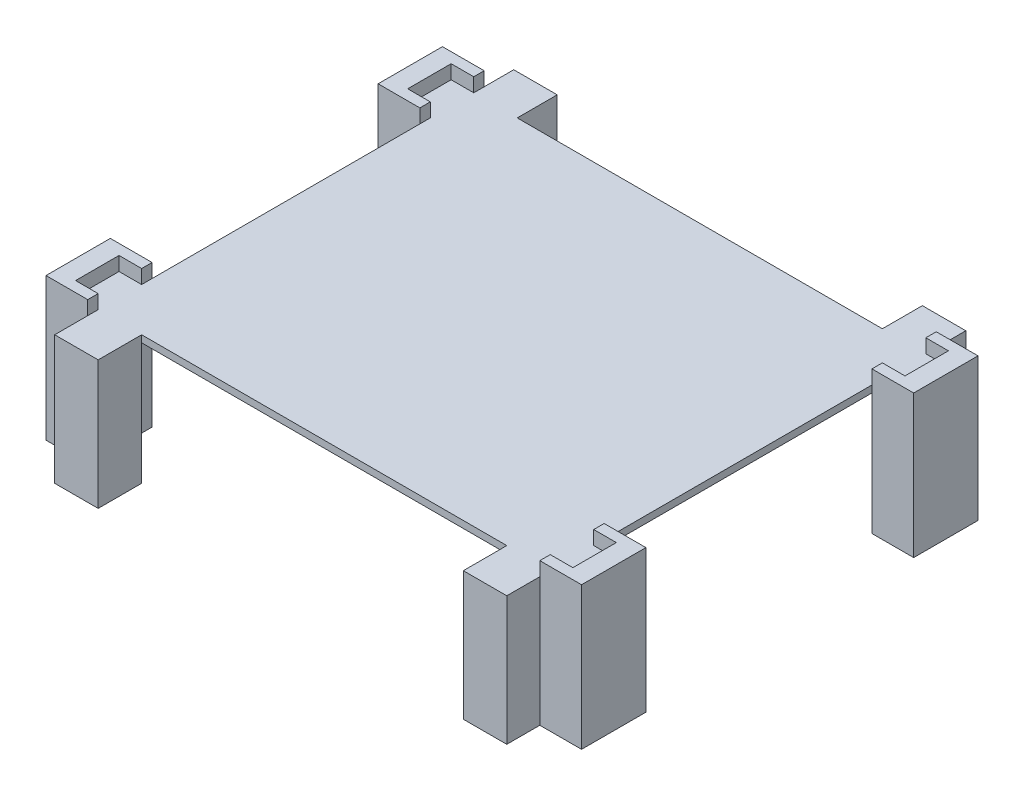
SolidWorks part; units mm, degrees
ref_plane "Front Plane" through (0, 0, 0) normal (0, 0, 1) x (1, 0, 0)
ref_plane "Top Plane" through (0, 0, 0) normal (0, 1, 0) x (1, 0, 0)
ref_plane "Right Plane" through (0, 0, 0) normal (1, 0, 0) x (0, 0, -1)
sketch "Sketch1" plane through (0, 0, 0) normal (0, 1, 0) x (1, 0, 0)
  line L0 (3, 0) -> (3, 3) construction
  line L1 (0, 0) -> (130, 0)
  line L2 (0, 0) -> (0, 108)
  line L3 (0, 108) -> (130, 108)
  line L4 (130, 0) -> (130, 108)
  line L5 (125.5, 108) -> (125.5, 105) construction
  line L6 (125.5, 105) -> (97.5, 105) construction
  line L8 (0, 0) -> (12.5, 0)
  line L9 (0, 0) -> (0, -12.5)
  line L10 (0, -12.5) -> (12.5, -12.5)
  line L11 (12.5, 0) -> (12.5, -12.5)
  line L12 (130, 0) -> (117.5, 0)
  line L13 (130, 0) -> (130, -12.5)
  line L14 (130, -12.5) -> (117.5, -12.5)
  line L15 (117.5, 0) -> (117.5, -12.5)
  line L16 (0, 108) -> (12.5, 108)
  line L17 (0, 108) -> (0, 119.5)
  line L18 (0, 119.5) -> (12.5, 119.5)
  line L19 (12.5, 108) -> (12.5, 119.5)
  line L20 (130, 108) -> (117.5, 108)
  line L21 (130, 108) -> (130, 119.5)
  line L22 (130, 119.5) -> (117.5, 119.5)
  line L23 (117.5, 108) -> (117.5, 119.5)
  circle A0 centre (3, 3) radius 1
  circle A1 centre (125.5, 105) radius 1
  circle A2 centre (97.5, 105) radius 1
  circle A3 centre (3, 3) radius 2
  circle A4 centre (97.5, 105) radius 2
  circle A5 centre (125.5, 105) radius 2
  point P7 (3, 1.5)
  point P11 (125.5, 106.5)
  point P30 (0, 0)
  dimension "D5" = 2
  dimension "D8" = 2
  dimension "D10" = 2
  dimension "D11" = 4
  dimension "D12" = 4
  dimension "D13" = 4
  dimension "D1" = 130
  dimension "D2" = 108
  dimension "D3" = 3
  dimension "D4" = 3
  dimension "D6" = 3
  dimension "D7" = 4.5
  dimension "D9" = 28
  dimension "D14" = 12.5
  dimension "D15" = 12.5
  dimension "D16" = 12.5
  dimension "D17" = 12.5
  dimension "D18" = 11.5
  dimension "D19" = 12.5
  dimension "D20" = 11.5
  dimension "D21" = 12.5
sketch "Sketch9" plane through (0, 3, 0) normal (0, 1, 0) x (1, 0, 0)
  line L7 (0, 0) -> (-6.5, 0)
  line L8 (0, 0) -> (0, 12.5)
  line L9 (0, 12.5) -> (-6.5, 12.5)
  line L10 (-6.5, 0) -> (-6.5, 12.5)
  line L11 (0, 108) -> (-6.5, 108)
  line L12 (0, 108) -> (0, 95.5)
  line L13 (0, 95.5) -> (-6.5, 95.5)
  line L14 (-6.5, 108) -> (-6.5, 95.5)
  line L15 (130, 0) -> (136.5, 0)
  line L16 (130, 0) -> (130, 12.5)
  line L17 (130, 12.5) -> (136.5, 12.5)
  line L18 (136.5, 0) -> (136.5, 12.5)
  line L19 (130, 108) -> (136.5, 108)
  line L20 (130, 108) -> (130, 95.5)
  line L21 (130, 95.5) -> (136.5, 95.5)
  line L22 (136.5, 108) -> (136.5, 95.5)
  line L43 (130, 12.5) -> (142, 12.5)
  line L44 (130, 12.5) -> (130, 15.5)
  line L45 (130, 15.5) -> (142, 15.5)
  line L46 (142, 12.5) -> (142, 15.5)
  line L47 (130, 0) -> (142, 0)
  line L48 (130, 0) -> (130, -3)
  line L49 (130, -3) -> (142, -3)
  line L50 (142, 0) -> (142, -3)
  line L51 (0, 0) -> (-12, 0)
  line L52 (0, 0) -> (0, -3)
  line L53 (0, -3) -> (-12, -3)
  line L54 (-12, 0) -> (-12, -3)
  line L55 (0, 12.5) -> (-12, 12.5)
  line L56 (0, 12.5) -> (0, 15.5)
  line L57 (0, 15.5) -> (-12, 15.5)
  line L58 (-12, 12.5) -> (-12, 15.5)
  line L59 (0, 95.5) -> (-12, 95.5)
  line L60 (0, 95.5) -> (0, 92.5)
  line L61 (0, 92.5) -> (-12, 92.5)
  line L62 (-12, 95.5) -> (-12, 92.5)
  line L63 (0, 108) -> (-12, 108)
  line L64 (0, 108) -> (0, 111)
  line L65 (0, 111) -> (-12, 111)
  line L66 (-12, 108) -> (-12, 111)
  line L67 (130, 108) -> (142, 108)
  line L68 (130, 108) -> (130, 111)
  line L69 (130, 111) -> (142, 111)
  line L70 (142, 108) -> (142, 111)
  line L71 (130, 95.5) -> (142, 95.5)
  line L72 (130, 95.5) -> (130, 92.5)
  line L73 (130, 92.5) -> (142, 92.5)
  line L74 (142, 95.5) -> (142, 92.5)
  line L75 (136.5, 0) -> (142, 0)
  line L76 (136.5, 0) -> (136.5, 12.5)
  line L77 (136.5, 12.5) -> (142, 12.5)
  line L78 (142, 0) -> (142, 12.5)
  line L79 (136.5, 95.5) -> (142, 95.5)
  line L80 (136.5, 95.5) -> (136.5, 108)
  line L81 (136.5, 108) -> (142, 108)
  line L82 (142, 95.5) -> (142, 108)
  line L83 (-6.5, 108) -> (-12, 108)
  line L84 (-6.5, 108) -> (-6.5, 95.5)
  line L85 (-6.5, 95.5) -> (-12, 95.5)
  line L86 (-12, 108) -> (-12, 95.5)
  line L87 (-6.5, 12.5) -> (-12, 12.5)
  line L88 (-6.5, 12.5) -> (-6.5, 0)
  line L89 (-6.5, 0) -> (-12, 0)
  line L90 (-12, 12.5) -> (-12, 0)
  dimension "D1" = 6.5
  dimension "D2" = 12.5
  dimension "D3" = 6.5
  dimension "D4" = 12.5
  dimension "D5" = 6.5
  dimension "D6" = 12.5
  dimension "D7" = 6.5
  dimension "D8" = 12.5
  dimension "D10" = 12
  dimension "D11" = 3
  dimension "D12" = 3
  dimension "D13" = 12
  dimension "D14" = 3
  dimension "D16" = 3
  dimension "D17" = 12
  dimension "D18" = 3
  dimension "D20" = 3
  dimension "D21" = 12
  dimension "D22" = 3
  dimension "D24" = 3
extrude "Boss-Extrude1" add sketch "Sketch9" along normal blind 4 contours L51 L54 L53 L52 L7 | L55 L90 L51 L10 | L58 L55 L9 L56 L57 | L43 L46 L45 L44 L17 | L47 L78 L43 L18 | L50 L47 L15 L48 L49 | L74 L71 L21 L72 L73 | L71 L82 L67 L22 | L67 L70 L69 L68 L19 | L59 L62 L61 L60 L13 | L63 L86 L59 L14 | L66 L63 L11 L64 L65
sketch "Sketch11" plane through (0, 3, 0) normal (0, -1, 0) x (1, 0, 0)
  line L1 (0, 3) -> (-12, 3)
  line L2 (0, 3) -> (0, -15.5)
  line L3 (0, -15.5) -> (-12, -15.5)
  line L4 (-12, 3) -> (-12, -15.5)
  line L5 (130, 3) -> (142, 3)
  line L6 (130, 3) -> (130, -15.5)
  line L7 (130, -15.5) -> (142, -15.5)
  line L8 (142, 3) -> (142, -15.5)
  line L9 (142, -111) -> (130, -111)
  line L10 (142, -111) -> (142, -92.5)
  line L11 (142, -92.5) -> (130, -92.5)
  line L12 (130, -111) -> (130, -92.5)
  line L13 (0, -111) -> (-12, -111)
  line L14 (0, -111) -> (0, -92.5)
  line L15 (0, -92.5) -> (-12, -92.5)
  line L16 (-12, -111) -> (-12, -92.5)
  line L17 (0, -108) -> (130, -108)
  line L18 (0, -108) -> (0, 0)
  line L19 (0, 0) -> (130, 0)
  line L20 (130, -108) -> (130, 0)
  line M5 (-6.5, 0) -> (0, 0)
  line M6 (0, 0) -> (0, 3)
  line M7 (0, 3) -> (-12, 3)
  line M8 (-12, 3) -> (-12, -15.5)
  line M9 (-12, -15.5) -> (0, -15.5)
  line M10 (0, -15.5) -> (0, -12.5)
  line M11 (0, -12.5) -> (-6.5, -12.5)
  line M12 (-6.5, -12.5) -> (-6.5, 0)
extrude "Boss-Extrude2" add sketch "Sketch11" along normal blind 2 contours L12 L20 L6 L19 L2 L18 L14 L17 M10 | L2 M5 M12 M11 | M12 M5 M6 M7 M8 M9 M10 M11 | L8 L5 L6 L7 | L12 L9 L10 L11 | L16 L13 L14 L15
sketch "Sketch12" plane through (0, 1, 0) normal (0, -1, 0) x (1, 0, 0)
  line L1 (130, 0) -> (117.5, 0)
  line L2 (130, 0) -> (130, 12.5)
  line L3 (130, 12.5) -> (117.5, 12.5)
  line L4 (117.5, 0) -> (117.5, 12.5)
  line L5 (130, -108) -> (117.5, -108)
  line L6 (130, -108) -> (130, -119.5)
  line L7 (130, -119.5) -> (117.5, -119.5)
  line L8 (117.5, -108) -> (117.5, -119.5)
  line L9 (0, -108) -> (12.5, -108)
  line L10 (0, -108) -> (0, -119.5)
  line L11 (0, -119.5) -> (12.5, -119.5)
  line L12 (12.5, -108) -> (12.5, -119.5)
  line L13 (12.5, 0) -> (0, 0)
  line L14 (12.5, 0) -> (12.5, 12.5)
  line L15 (12.5, 12.5) -> (0, 12.5)
  line L16 (0, 0) -> (0, 12.5)
  line M9 (130, 0) -> (0, 0)
  line M10 (0, 0) -> (0, 3)
  line M18 (0, -111) -> (0, -108)
  line M19 (0, -108) -> (130, -108)
  line M20 (130, -108) -> (130, -111)
  line M28 (130, 3) -> (130, 0)
extrude "Boss-Extrude3" add sketch "Sketch12" against normal blind 2 contours L12 L10 L11 M19 M18 | L16 L14 L15 M10 M9 | L4 L2 L3 M9 M28 | L8 L7 L6 M19 M20
sketch "Sketch13" plane through (0, 1, 0) normal (0, -1, 0) x (-1, 0, 0)
  line L0 (-142, -3) -> (-142, 15.5) construction
  line L1 (0, -12.5) -> (-12.5, -12.5)
  line L2 (0, -12.5) -> (0, 0)
  line L3 (0, 0) -> (-12.5, 0)
  line L4 (-12.5, -12.5) -> (-12.5, 0)
  line L5 (12, -3) -> (0, -3)
  line L6 (12, -3) -> (12, 15.5)
  line L7 (12, 15.5) -> (0, 15.5)
  line L8 (0, -3) -> (0, 15.5)
  line L9 (0, 0) -> (-130, 0)
  line L10 (0, 0) -> (0, 108)
  line L11 (0, 108) -> (-130, 108)
  line L12 (-130, 0) -> (-130, 108)
  line L13 (-117.5, 108) -> (-130, 108)
  line L14 (-117.5, 108) -> (-117.5, 119.5)
  line L15 (-117.5, 119.5) -> (-130, 119.5)
  line L16 (-130, 108) -> (-130, 119.5)
  line L17 (-130, 92.5) -> (-142, 92.5)
  line L18 (-130, 92.5) -> (-130, 111)
  line L19 (-130, 111) -> (-142, 111)
  line L20 (-142, 92.5) -> (-142, 111)
  line L21 (-130, -3) -> (-142, -3)
  line L22 (-130, -3) -> (-130, 15.5)
  line L23 (-130, 15.5) -> (-142, 15.5)
  line L24 (-142, -3) -> (-142, 15.5)
  line L26 (-117.5, -12.5) -> (-130, -12.5)
  line L27 (-117.5, -12.5) -> (-117.5, 0)
  line L28 (-117.5, 0) -> (-130, 0)
  line L29 (-130, -12.5) -> (-130, 0)
  line L30 (0, 108) -> (-12.5, 108)
  line L31 (0, 108) -> (0, 119.5)
  line L32 (0, 119.5) -> (-12.5, 119.5)
  line L33 (-12.5, 108) -> (-12.5, 119.5)
  line L34 (12, 92.5) -> (0, 92.5)
  line L35 (12, 92.5) -> (12, 111)
  line L36 (12, 111) -> (0, 111)
  line L37 (0, 92.5) -> (0, 111)
  line M5 (0, -12.5) -> (0, -3)
  line M6 (0, -3) -> (12, -3)
  line M7 (12, -3) -> (12, 15.5)
  line M8 (12, 15.5) -> (0, 15.5)
  line M10 (0, 92.5) -> (12, 92.5)
  line M11 (12, 92.5) -> (12, 111)
  line M12 (12, 111) -> (0, 111)
  line M13 (0, 111) -> (0, 119.5)
  line M14 (0, 119.5) -> (-12.5, 119.5)
  line M15 (-12.5, 119.5) -> (-12.5, 108)
  line M17 (-117.5, 108) -> (-117.5, 119.5)
  line M18 (-117.5, 119.5) -> (-130, 119.5)
  line M19 (-130, 119.5) -> (-130, 111)
  line M20 (-130, 111) -> (-142, 111)
  line M21 (-142, 111) -> (-142, 92.5)
  line M22 (-142, 92.5) -> (-130, 92.5)
  line M24 (-130, 15.5) -> (-142, 15.5)
  line M25 (-142, 15.5) -> (-142, -3)
  line M26 (-142, -3) -> (-130, -3)
  line M27 (-130, -3) -> (-130, -12.5)
  line M28 (-130, -12.5) -> (-117.5, -12.5)
  line M29 (-117.5, -12.5) -> (-117.5, 0)
  line M31 (-12.5, 0) -> (-12.5, -12.5)
  line M32 (-12.5, -12.5) -> (0, -12.5)
extrude "Boss-Extrude4" add sketch "Sketch13" along normal blind 35 contours L2 L3 M31 M32 M5 | L8 L2 M6 M7 M8 | L22 L9 M27 M28 M29 | L22 L12 M26 M24 M25 | L12 L16 M20 M21 M22 | L16 L11 M17 M18 M19 | L11 L31 M13 M14 M15 | L31 L10 M10 M11 M12
